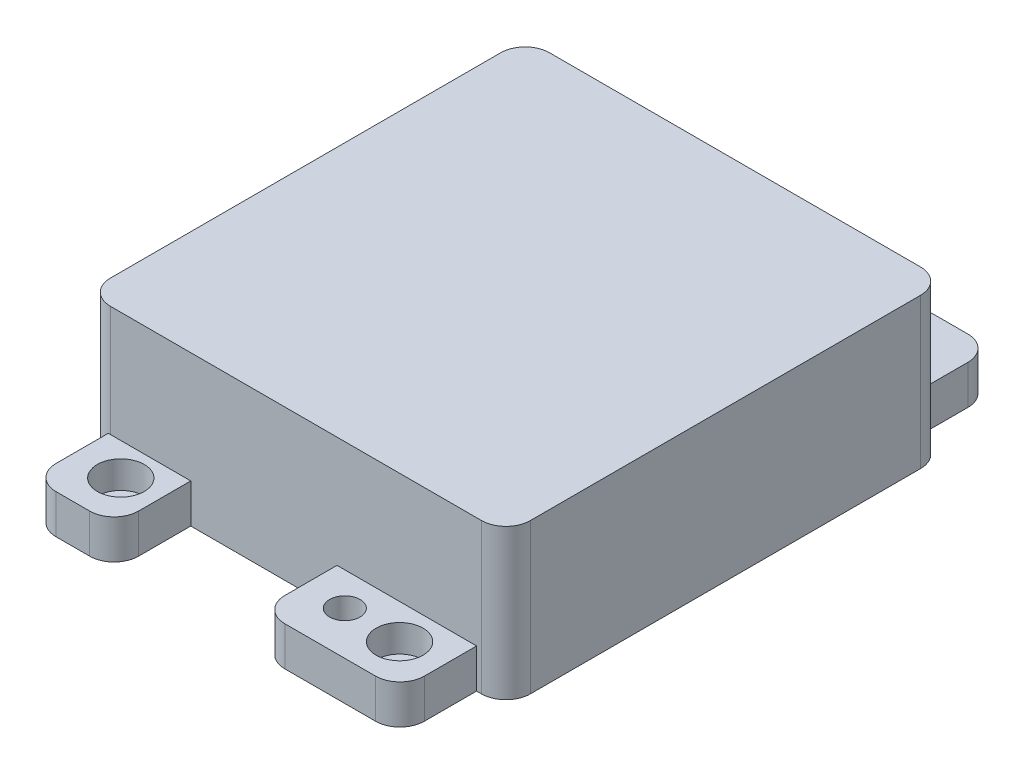
SolidWorks part; units mm, degrees
ref_plane "Front Plane" through (0, 0, 0) normal (0, 0, 1) x (1, 0, 0)
ref_plane "Top Plane" through (0, 0, 0) normal (0, 1, 0) x (1, 0, 0)
ref_plane "Right Plane" through (0, 0, 0) normal (1, 0, 0) x (0, 0, -1)
sketch "Sketch1" plane through (0, 0, 0) normal (0, 1, 0) x (1, 0, 0)
  line L1 (-13.6398, -14.2621) -> (13.6398, -14.2621)
  line L2 (-13.6398, -14.2621) -> (-13.6398, 14.2621)
  line L3 (-13.6398, 14.2621) -> (13.6398, 14.2621)
  line L4 (13.6398, -14.2621) -> (13.6398, 14.2621)
  line L5 (-13.6398, -14.2621) -> (13.6398, 14.2621) construction
  line L6 (-13.6398, 14.2621) -> (13.6398, -14.2621) construction
  point P0 (0, 0)
  dimension "D1" = 27.2796
  dimension "D2" = 28.5242
extrude "Enclosure" add sketch "Sketch1" along normal blind 9.7536
sketch "Sketch2" plane through (0, 0, 0) normal (0, 1, 0) x (1, 0, 0)
  line L0 (13.6398, 14.2621) -> (-13.6398, 14.2621) construction
  line L1 (-12.192, 14.2621) -> (-3.1242, 14.2621)
  line L2 (-12.192, 14.2621) -> (-12.192, 19.2405)
  line L3 (-12.192, 19.2405) -> (-3.1242, 19.2405)
  line L4 (-3.1242, 14.2621) -> (-3.1242, 19.2405)
  line L5 (-13.6398, -14.2621) -> (13.6398, -14.2621) construction
  line L6 (6.3754, 14.2621) -> (11.7348, 14.2621)
  line L7 (6.3754, 14.2621) -> (6.3754, 19.2405)
  line L8 (6.3754, 19.2405) -> (11.7348, 19.2405)
  line L9 (11.7348, 14.2621) -> (11.7348, 19.2405)
  line L10 (-12.192, -14.2621) -> (-6.8326, -14.2621)
  line L11 (-12.192, -14.2621) -> (-12.192, -19.2405)
  line L12 (-12.192, -19.2405) -> (-6.8326, -19.2405)
  line L13 (-6.8326, -14.2621) -> (-6.8326, -19.2405)
  line L14 (13.6398, -14.2621) -> (13.6398, 14.2621) construction
  line L15 (11.7348, -14.2621) -> (2.667, -14.2621)
  line L16 (11.7348, -14.2621) -> (11.7348, -19.2405)
  line L17 (11.7348, -19.2405) -> (2.667, -19.2405)
  line L18 (2.667, -14.2621) -> (2.667, -19.2405)
  dimension "D1" = 9.0678
  dimension "D2" = 4.9784
  dimension "D3" = 5.3594
  dimension "D4" = 1.905
  dimension "D5" = 23.9268
extrude "Mounting Tabs" add sketch "Sketch2" along normal blind 2.54
sketch "Sketch3" plane through (0, 2.54, 0) normal (0, 1, 0) x (1, 0, 0)
  line L0 (-12.192, 17.4625) -> (-3.1242, 17.4625) construction
  line L1 (-3.1242, 14.2621) -> (-3.1242, 19.2405) construction
  line L2 (-3.1242, 19.2405) -> (-12.192, 19.2405) construction
  line L3 (-4.8006, 19.2405) -> (-4.8006, 14.2621) construction
  line L4 (-12.192, 14.2621) -> (-3.1242, 14.2621) construction
  line L5 (-12.192, 19.2405) -> (-12.192, 14.2621) construction
  line L6 (4.3434, -14.2621) -> (4.3434, -19.2405) construction
  line L7 (11.7348, -14.2621) -> (2.667, -14.2621) construction
  line L8 (2.667, -19.2405) -> (11.7348, -19.2405) construction
  line L9 (2.667, -14.2621) -> (2.667, -19.2405) construction
  line L10 (2.667, -17.4117) -> (11.7348, -17.4117) construction
  line L11 (11.7348, -19.2405) -> (11.7348, -14.2621) construction
  circle A0 centre (-5.842, 16.4211) radius 1.0414
  circle A1 centre (5.334, -16.4211) radius 0.9906
  dimension "D1" = 2.0828
  dimension "D4" = 1.9812
  dimension "D2" = 1.778
  dimension "D3" = 1.6764
  dimension "D5" = 1.6764
  dimension "D6" = 1.8288
extrude "Small Mounting Holes" cut sketch "Sketch3" against normal up to next
sketch "Sketch4" plane through (0, 0, 0) normal (0, -1, 0) x (1, 0, 0)
  line L0 (-12.192, -17.2339) -> (-3.1242, -17.2339) construction
  line L1 (-12.192, -19.2405) -> (-12.192, -14.2621) construction
  line L2 (-3.1242, -14.2621) -> (-3.1242, -19.2405) construction
  line L3 (-10.033, -19.2405) -> (-10.033, -14.026) construction
  line L4 (-3.1242, -19.2405) -> (-12.192, -19.2405) construction
  line L5 (9.7282, -19.2405) -> (9.7282, -14.2791) construction
  line L6 (11.7348, -19.2405) -> (6.3754, -19.2405) construction
  line L7 (11.7348, -17.2339) -> (6.3754, -17.2339) construction
  line L8 (11.7348, -14.2621) -> (11.7348, -19.2405) construction
  line L9 (6.3754, -19.2405) -> (6.3754, -14.2621) construction
  line L10 (-12.192, 17.1323) -> (-6.8326, 17.1323) construction
  line L11 (-12.192, 14.2621) -> (-12.192, 19.2405) construction
  line L12 (-6.8326, 19.2405) -> (-6.8326, 14.2621) construction
  line L13 (2.667, 17.3101) -> (11.7348, 17.3101) construction
  line L16 (9.779, 19.2405) -> (9.779, 14.3298) construction
  line L17 (2.667, 19.2405) -> (11.7348, 19.2405) construction
  line L18 (-10.033, 19.2405) -> (-10.033, 15.6463) construction
  line L20 (-12.192, 19.2405) -> (-6.8326, 19.2405) construction
  line L21 (2.667, 14.2621) -> (2.667, 19.2405) construction
  line L22 (11.7348, 19.2405) -> (11.7348, 14.2621) construction
  circle A0 centre (-9.271, 16.3703) radius 0.762
  circle A1 centre (8.9916, 16.5227) radius 0.7874
  circle A2 centre (8.9662, -16.4719) radius 0.762
  circle A3 centre (-9.3091, -16.51) radius 0.7239
  dimension "D1" = 1.524
  dimension "D2" = 1.4478
  dimension "D3" = 1.524
  dimension "D4" = 1.5748
  dimension "D5" = 2.159
  dimension "D6" = 2.159
  dimension "D7" = 2.1082
  dimension "D8" = 1.9304
  dimension "D9" = 1.9558
  dimension "D10" = 2.0066
  dimension "D11" = 2.0066
  dimension "D12" = 2.0066
extrude "Large Mounting Holes" cut sketch "Sketch4" against normal up to next
sketch "Sketch5" plane through (0, 2.54, 0) normal (0, 1, 0) x (1, 0, 0)
  circle A0 centre (-9.271, -16.3703) radius 1.524
  circle A1 centre (8.9916, -16.5227) radius 1.524
  circle A2 centre (-9.3091, 16.51) radius 1.524
  dimension "D1" = 3.048
extrude "Cut-Extrude1" cut sketch "Sketch5" against normal blind 1.778
fillet "Fillet1" radius 1.5875 4 edges at (-13.6398, 4.8768, -14.2621) (13.6398, 4.8768, -14.2621) (-13.6398, 4.8768, 14.2621) (13.6398, 4.8768, 14.2621)
fillet "Fillet2" radius 1.5875 8 edges at (-12.192, 1.27, 19.2405) (2.667, 1.27, 19.2405) (-6.8326, 1.27, 19.2405) (11.7348, 1.27, 19.2405) (-12.192, 1.27, -19.2405) (-3.1242, 1.27, -19.2405) (6.3754, 1.27, -19.2405) (11.7348, 1.27, -19.2405)
sketch "Sketch6" plane through (0, 0, 0) normal (0, -1, 0) x (1, 0, 0)
  line L0 (-10.6045, 19.2405) -> (-8.4201, 19.2405) construction
  line L1 (-13.6398, -12.6746) -> (-13.6398, 12.6746) construction
  point P0 (-9.271, 16.3703)
  point P1 (-9.3091, -16.51)
  point P3 (-5.842, -16.4211)
  point P5 (5.334, 16.4211)
  point P7 (9.0959, 16.4211)
  point P11 (-9.5123, 19.2405)
  dimension "D1" = 35.7505
  dimension "D2" = 4.3688
  dimension "D3" = 7.7978
  dimension "D4" = 18.9738
  dimension "D5" = 2.8702
  dimension "D6" = 22.7357
